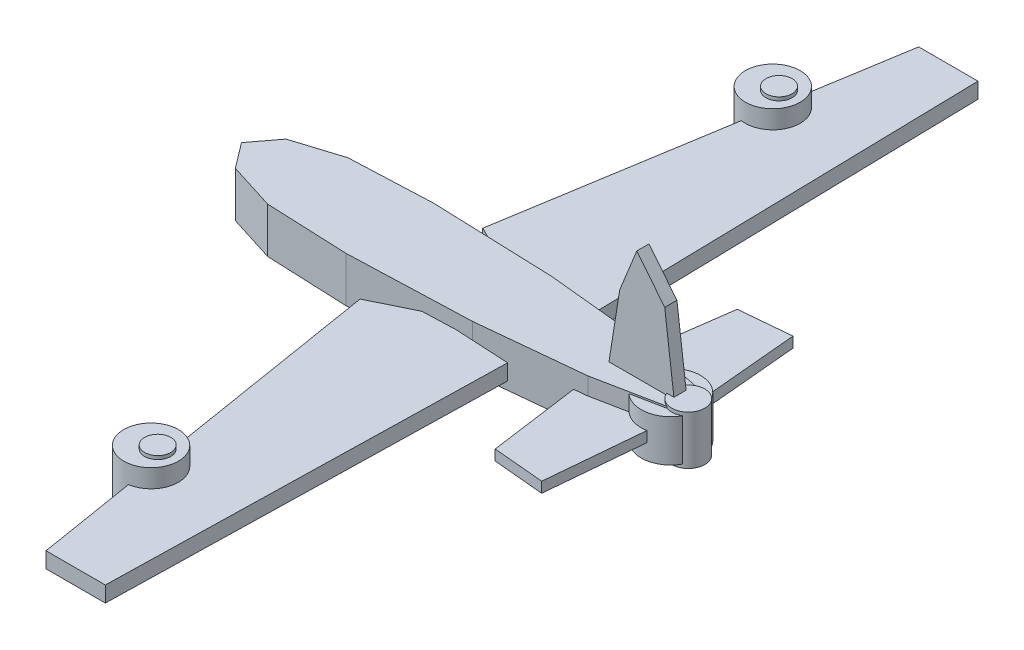
SolidWorks part; units mm, degrees
ref_plane "Front Plane" through (0, 0, 0) normal (0, 0, 1) x (1, 0, 0)
ref_plane "Top Plane" through (0, 0, 0) normal (0, 1, 0) x (1, 0, 0)
ref_plane "Right Plane" through (0, 0, 0) normal (1, 0, 0) x (0, 0, -1)
sketch "Sketch1" plane through (0, 0, 0) normal (0, 1, 0) x (1, 0, 0)
  line L0 (-1300, 0) -> (-1190, 145)
  line L1 (-1190, 145) -> (-920, 230)
  line L2 (-920, 230) -> (-450, 250)
  line L3 (-450, 250) -> (250, 225)
  line L4 (250, 225) -> (850, 165)
  line L5 (850, 165) -> (1250, 85)
  line L6 (1250, 85) -> (1300, 0)
  line L7 (1300, 0) -> (1250, -85)
  line L8 (1250, -85) -> (850, -165)
  line L9 (850, -165) -> (250, -225)
  line L10 (250, -225) -> (-450, -250)
  line L11 (-450, -250) -> (-920, -230)
  line L12 (-920, -230) -> (-1190, -145)
  line L13 (-1190, -145) -> (-1300, 0)
extrude "Boss-Extrude1" add sketch "Sketch1" along normal mid plane 260 separate body
sketch "Sketch2" plane through (0, 0, 0) normal (0, 1, 0) x (1, 0, 0)
  line L0 (0, 220) -> (470, 245)
  line L1 (470, 245) -> (420, 2500)
  line L2 (420, 2500) -> (80, 2500)
  line L3 (80, 2500) -> (-180, 900)
  line L4 (-180, 900) -> (-269.1338, 351.4842)
  line L5 (-269.1338, 351.4842) -> (0, 220)
extrude "Boss-Extrude2" add sketch "Sketch2" along normal mid plane 90 separate body
sketch "Sketch3" plane through (0, 0, 0) normal (0, 1, 0) x (1, 0, 0)
  line L0 (0, -220) -> (470, -245)
  line L1 (470, -245) -> (420, -2500)
  line L2 (420, -2500) -> (80, -2500)
  line L3 (80, -2500) -> (-180, -900)
  line L4 (-180, -900) -> (-269.1338, -351.4842)
  line L5 (-269.1338, -351.4842) -> (0, -220)
extrude "Boss-Extrude3" add sketch "Sketch3" along normal mid plane 90 separate body
sketch "Sketch4" plane through (0, 0, 0) normal (0, 1, 0) x (1, 0, 0)
  line L0 (760, 60) -> (1200, 60)
  line L1 (1200, 60) -> (1140, 720)
  line L2 (1140, 720) -> (846.9672, 693.3607)
  line L3 (846.9672, 693.3607) -> (760, 60)
extrude "Boss-Extrude4" add sketch "Sketch4" along normal mid plane 60 separate body
sketch "Sketch5" plane through (0, 0, 0) normal (0, 1, 0) x (1, 0, 0)
  line L0 (760, -60) -> (1200, -60)
  line L1 (1200, -60) -> (1140, -720)
  line L2 (1140, -720) -> (846.9672, -693.3607)
  line L3 (846.9672, -693.3607) -> (760, -60)
extrude "Boss-Extrude5" add sketch "Sketch5" along normal mid plane 60 separate body
sketch "Sketch6" plane through (0, 0, 0) normal (0, 0, 1) x (1, 0, 0)
  line L0 (820, 0) -> (1230, 0)
  line L1 (1230, 0) -> (1160, 560)
  line L2 (1160, 560) -> (1000, 760)
  line L3 (1000, 760) -> (901.9512, 517.561)
  line L4 (901.9512, 517.561) -> (820, 0)
extrude "Boss-Extrude6" add sketch "Sketch6" along normal mid plane 70 separate body
sketch "Sketch7" plane through (0, 0, 0) normal (0, 1, 0) x (1, 0, 0)
  line L0 (80, 2500) -> (-269.1338, 351.4842) construction
  circle A0 centre (-36.8199, 1781.1082) radius 156.8199
extrude "Boss-Extrude7" add sketch "Sketch7" along normal mid plane 300 separate body
sketch "Sketch8" plane through (0, 0, 0) normal (0, 1, 0) x (1, 0, 0)
  line L0 (-269.1338, -351.4842) -> (80, -2500) construction
  circle A0 centre (-36.8199, -1781.1082) radius 156.8199
extrude "Boss-Extrude8" add sketch "Sketch8" along normal mid plane 300 separate body
sketch "Sketch9" plane through (0, 0, 0) normal (0, 1, 0) x (1, 0, 0)
  line L0 (1160, -35) -> (1160, 35) construction
  circle A0 centre (1160, 0) radius 170
extrude "Boss-Extrude9" add sketch "Sketch9" along normal mid plane 240 separate body
sketch "Sketch10" plane through (0, 0, 0) normal (0, 1, 0) x (1, 0, 0)
  circle A0 centre (0, 1780) radius 75
extrude "Boss-Extrude10" add sketch "Sketch10" along normal mid plane 340 separate body
sketch "Sketch11" plane through (0, 0, 0) normal (0, 1, 0) x (1, 0, 0)
  circle A0 centre (0, -1780) radius 75
extrude "Boss-Extrude11" add sketch "Sketch11" along normal mid plane 340 separate body
sketch "Sketch12" plane through (0, 0, 0) normal (0, 1, 0) x (1, 0, 0)
  circle A0 centre (1260, 0) radius 95
extrude "Boss-Extrude12" add sketch "Sketch12" along normal mid plane 280 separate body
sketch "Sketch13" plane through (0, 0, 0) normal (0, 1, 0) x (1, 0, 0)
  circle A0 centre (-1080, 0) radius 125
extrude "Boss-Extrude13" add sketch "Sketch13" along normal mid plane 90 separate body
